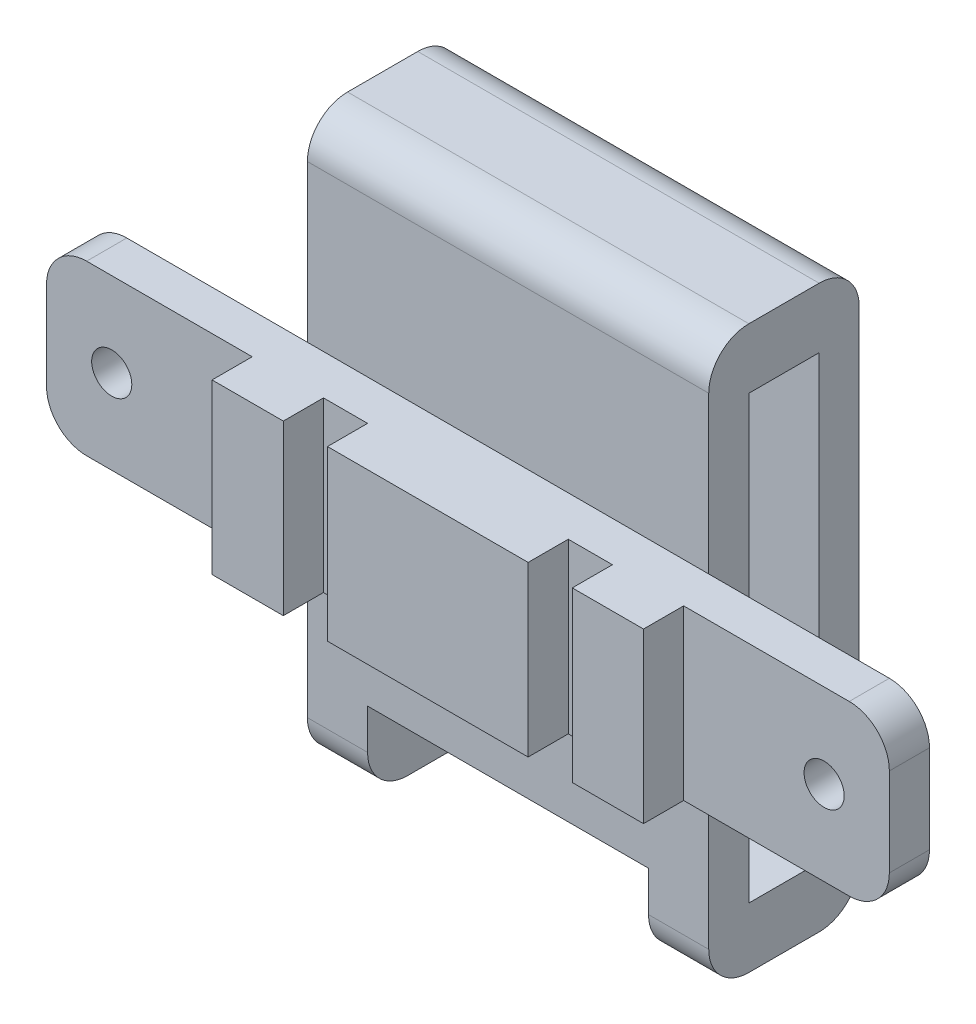
SolidWorks part; units mm, degrees
ref_plane "Front Plane" through (0, 0, 0) normal (0, 0, 1) x (1, 0, 0)
ref_plane "Top Plane" through (0, 0, 0) normal (0, 1, 0) x (1, 0, 0)
ref_plane "Right Plane" through (0, 0, 0) normal (1, 0, 0) x (0, 0, -1)
sketch "Sketch2" plane through (0, 0, 0) normal (0, 0, 1) x (1, 0, 0)
  line L1 (-21, 4.2) -> (21, 4.2)
  line L2 (-21, 4.2) -> (-21, -4.2)
  line L3 (-21, -4.2) -> (21, -4.2)
  line L4 (21, 4.2) -> (21, -4.2)
  dimension "D1" = 4.2
  dimension "D2" = 8.4
  dimension "D3" = 42
  dimension "D4" = 21
extrude "Boss-Extrude1" add sketch "Sketch2" along normal blind 2
sketch "Sketch3" plane through (0, 0, 2) normal (0, 0, 1) x (1, 0, 0)
  line L0 (21, 4.2) -> (-21, 4.2) construction
  line L1 (-10.75, 4.2) -> (-7.2, 4.2)
  line L2 (-10.75, 4.2) -> (-10.75, -4.2)
  line L3 (-10.75, -4.2) -> (-7.2, -4.2)
  line L4 (10.75, 4.2) -> (10.75, -4.2)
  line L5 (-21, -4.2) -> (21, -4.2) construction
  line L6 (-5, 4.2) -> (5, 4.2)
  line L8 (-7.2, 4.2) -> (-7.2, -4.2)
  line L10 (-5, 4.2) -> (-5, -4.2)
  line L12 (5, 4.2) -> (5, -4.2)
  line L14 (7.2, 4.2) -> (7.2, -4.2)
  line L15 (-5, -4.2) -> (5, -4.2)
  line L16 (7.2, -4.2) -> (10.75, -4.2)
  line L17 (7.2, 4.2) -> (10.75, 4.2)
  dimension "D1" = 10.75
  dimension "D2" = 10.75
  dimension "D3" = 10
  dimension "D4" = 5
  dimension "D5" = 2.2
  dimension "D6" = 2.2
extrude "Boss-Extrude2" add sketch "Sketch3" along normal blind 2
fillet "Fillet1" radius 2 4 edges at (21, -4.2, 1) (21, 4.2, 1) (-21, -4.2, 1) (-21, 4.2, 1)
sketch "Sketch4" plane through (0, 0, 2) normal (0, 0, 1) x (1, 0, 0)
  line L0 (-21, 0) -> (21, 0) construction
  line L1 (-21, 2.2) -> (-21, -2.2) construction
  line L2 (21, -2.2) -> (21, 2.2) construction
  circle A0 centre (-17.75, 0) radius 1
  circle A1 centre (17.75, 0) radius 1
  dimension "D1" = 2
  dimension "D2" = 2
  dimension "D3" = 35.5
  dimension "D4" = 17.75
extrude "Cut-Extrude1" cut sketch "Sketch4" against normal up to surface (2 mm away) up to face at (0, 0, 0)
sketch "Sketch5" plane through (0, 0, 0) normal (0, 0, -1) x (-1, 0, 0)
  line L1 (10, -14) -> (-10, -14)
  line L2 (10, -14) -> (10, 14)
  line L3 (10, 14) -> (-10, 14)
  line L4 (-10, -14) -> (-10, 14)
  dimension "D1" = 10
  dimension "D2" = 10
  dimension "D3" = 28
  dimension "D4" = 14
extrude "Boss-Extrude3" add sketch "Sketch5" along normal blind 7.5
fillet "Fillet2" radius 2 4 edges at (0, -14, -7.5) (0, 14, -7.5) (0, 14, 0) (0, -14, 0)
sketch "Sketch6" plane through (-10, 0, 0) normal (-1, 0, 0) x (0, 0, 1)
  line L0 (-7.5, 0) -> (4, 0) construction
  line L1 (-2, 11) -> (-5.5, 11)
  line L2 (-2, 11) -> (-2, -11)
  line L3 (-2, -11) -> (-5.5, -11)
  line L4 (-5.5, 11) -> (-5.5, -11)
  line L5 (-7.5, -12) -> (-7.5, 12) construction
  line L6 (4, 4.2) -> (4, -4.2) construction
  line L7 (0, -12) -> (0, -4.2) construction
  dimension "D1" = 11
  dimension "D2" = 11
  dimension "D3" = 2
  dimension "D4" = 2
extrude "Cut-Extrude2" cut sketch "Sketch6" against normal up to surface (20 mm away) up to face at (10, 0, -3)
sketch "Sketch7" plane through (0, 0, 0) normal (0, 0, 1) x (1, 0, 0)
  line L0 (10, -14) -> (-10, -14) construction
  line L1 (-7, -14) -> (7, -14)
  line L2 (-7, -14) -> (-7, -10)
  line L3 (-7, -10) -> (7, -10)
  line L4 (7, -14) -> (7, -10)
  line L5 (10, -14) -> (10, -12) construction
  line L6 (-10, -12) -> (-10, -14) construction
  dimension "D1" = 3
  dimension "D2" = 3
  dimension "D3" = 4
extrude "Cut-Extrude3" cut sketch "Sketch7" against normal blind 10
